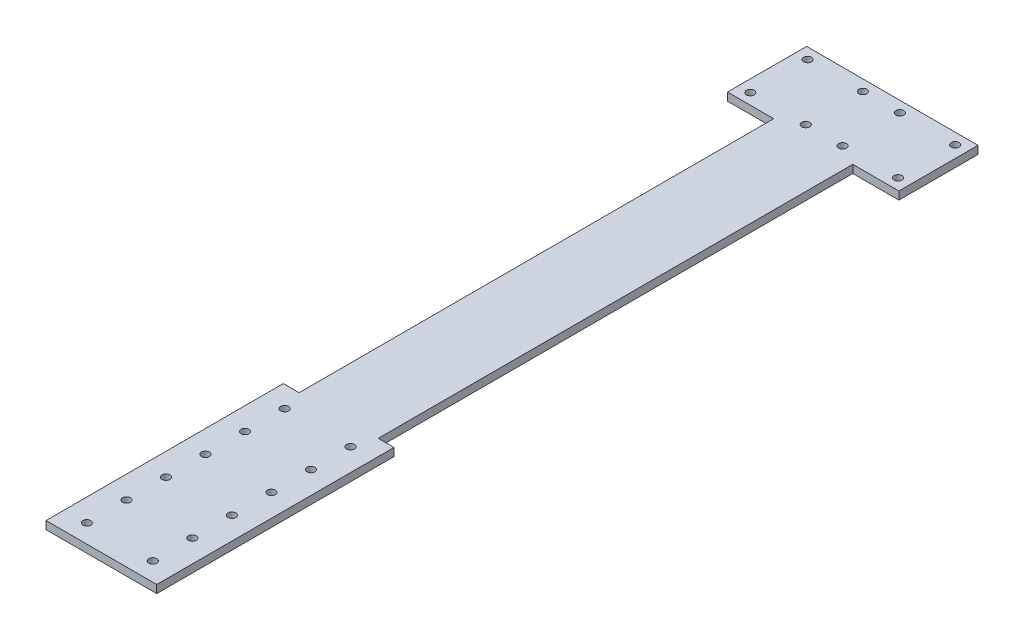
SolidWorks part; units mm, degrees
ref_plane "Front Plane" through (0, 0, 0) normal (0, 0, 1) x (1, 0, 0)
ref_plane "Top Plane" through (0, 0, 0) normal (0, 1, 0) x (1, 0, 0)
ref_plane "Right Plane" through (0, 0, 0) normal (1, 0, 0) x (0, 0, -1)
sketch "Sketch1" plane through (0, 0, 0) normal (0, 1, 0) x (1, 0, 0)
  line L0 (0, 0) -> (0, 300) construction
  line L1 (32.5, 300) -> (-32.5, 300)
  line L2 (-32.5, 300) -> (-32.5, 270)
  line L3 (-32.5, 270) -> (-15, 270)
  line L4 (-15, 270) -> (-15, 90)
  line L5 (-15, 90) -> (-21, 90)
  line L6 (-21, 90) -> (-21, 0)
  line L7 (-21, 0) -> (21, 0)
  line L8 (21, 90) -> (21, 0)
  line L9 (15, 90) -> (21, 90)
  line L10 (15, 270) -> (15, 90)
  line L11 (32.5, 270) -> (15, 270)
  line L12 (32.5, 300) -> (32.5, 270)
  dimension "D1" = 65
  dimension "D2" = 30
  dimension "D3" = 42
  dimension "D4" = 30
  dimension "D5" = 90
  dimension "D6" = 180
extrude "Boss-Extrude1" add sketch "Sketch1" along normal blind 3
sketch "Sketch2" plane through (0, 3, 0) normal (0, 1, 0) x (1, 0, 0)
  line L0 (0, 300) -> (0, 0) construction
  line L1 (32.5, 300) -> (-32.5, 300) construction
  line L2 (-28, 300) -> (-28, 274.15) construction
  line L3 (-7, 300) -> (-7, 274.15) construction
  line L4 (-28, 295.85) -> (-7, 295.85) construction
  line L5 (-17.5, 295.85) -> (-17.5, 130.7949) construction
  line L6 (-28, 285) -> (-7, 285) construction
  line L7 (-32.5, 285) -> (32.5, 285) construction
  line L8 (-32.5, 300) -> (-32.5, 270) construction
  line L9 (32.5, 270) -> (32.5, 300) construction
  circle A0 centre (-28, 295.85) radius 1.5
  circle A1 centre (-7, 295.85) radius 1.5
  circle A2 centre (-28, 274.15) radius 1.5
  circle A3 centre (-7, 274.15) radius 1.5
  dimension "D3" = 21.7
  dimension "D4" = 3
  dimension "D1" = 21
  dimension "D2" = 17.5
extrude "Cut-Extrude1" cut sketch "Sketch2" against normal through all both and the other way through all
mirror "Mirror1" about plane through (0, 0, 0) normal (1, 0, 0) of "Cut-Extrude1"
sketch "Sketch3" plane through (0, 3, 0) normal (0, 1, 0) x (1, 0, 0)
  line L0 (-12.5, 90) -> (-12.5, 0)
  line L1 (-15, 90) -> (-21, 90) construction
  line L2 (-21, 0) -> (21, 0) construction
  line L3 (0, 0) -> (0, 300) construction
  line L4 (32.5, 300) -> (-32.5, 300) construction
  circle A0 centre (-12.5, 82) radius 1.5
  circle A11 centre (12.5, 82) radius 1.5
  dimension "D1" = 3
  dimension "D2" = 25
  dimension "D3" = 8
extrude "Cut-Extrude2" cut sketch "Sketch3" against normal through all both and the other way through all contours L0 A0 | L0 A0 | A11
pattern_linear "LPattern1" count 6 spacing 15 along (0, 0, 1) of "Cut-Extrude2"
